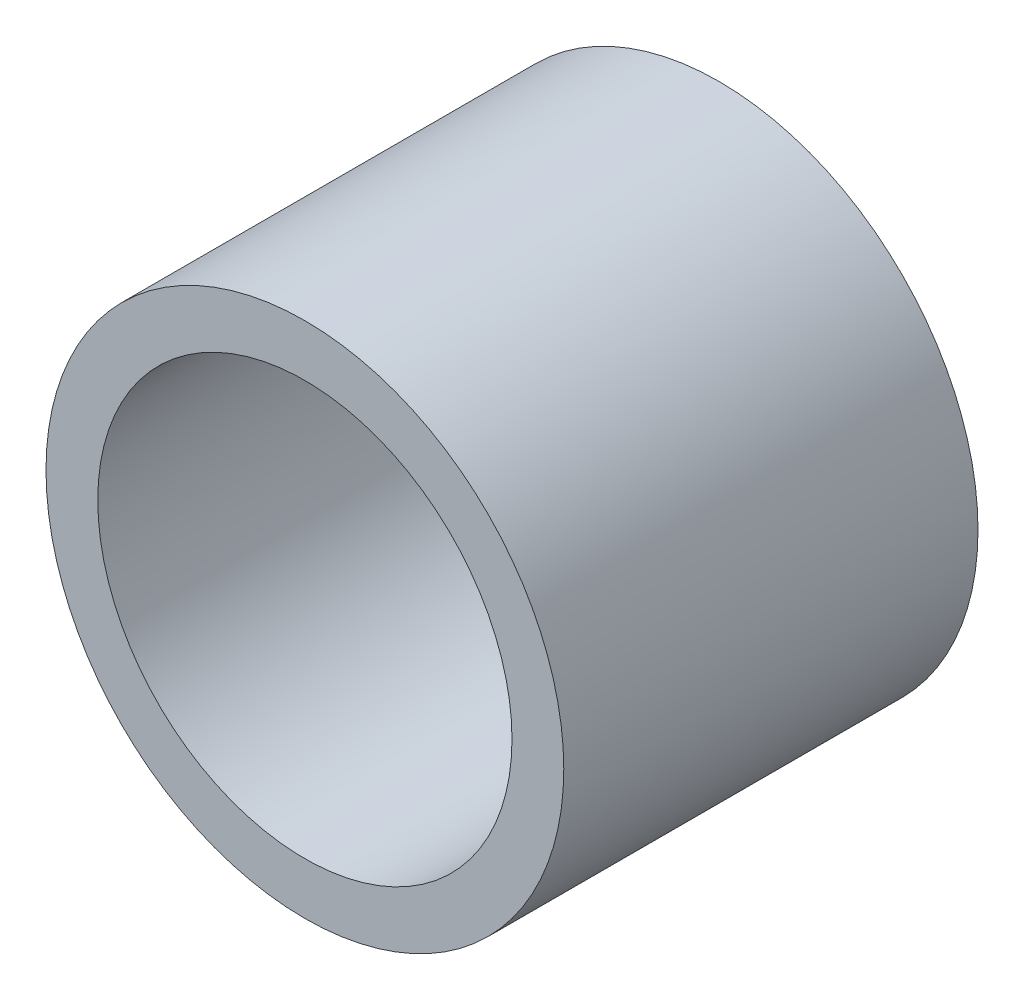
SolidWorks part; units mm, degrees
ref_plane "Plan de face" through (0, 0, 0) normal (0, 0, 1) x (1, 0, 0)
ref_plane "Plan de dessus" through (0, 0, 0) normal (0, 1, 0) x (1, 0, 0)
ref_plane "Plan de droite" through (0, 0, 0) normal (1, 0, 0) x (0, 0, -1)
sketch "Esquisse1" plane through (0, 0, 0) normal (0, 0, 1) x (1, 0, 0)
  circle A0 centre (0, 0) radius 31.75
extrude "Boss.-Extru.1" add sketch "Esquisse1" along normal blind 50.8
sketch "Esquisse4" plane through (0, 0, 50.8) normal (0, 0, 1) x (1, 0, 0)
  circle A0 centre (0, 0) radius 25.4
extrude "Enlèv. mat.-Extru.1" cut sketch "Esquisse4" against normal blind 43.45
sketch "Esquisse5" plane through (0, 0, 0) normal (0, 0, -1) x (-1, 0, 0)
  circle A0 centre (0, 0) radius 6.35
extrude "Enlèv. mat.-Extru.3" cut sketch "Esquisse5" against normal blind 7.35
